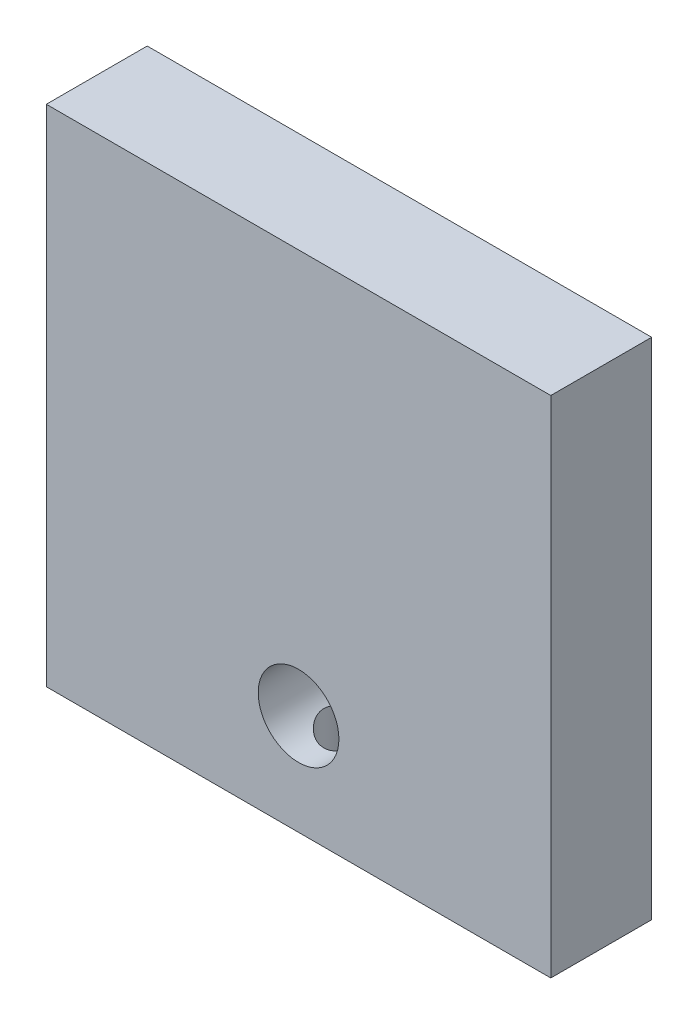
SolidWorks part; units mm, degrees
material "СТЕКЛОПЛАСТИК"
ref_plane "Спереди" through (0, 0, 0) normal (0, 0, 1) x (1, 0, 0)
ref_plane "Сверху" through (0, 0, 0) normal (0, 1, 0) x (1, 0, 0)
ref_plane "Справа" through (0, 0, 0) normal (1, 0, 0) x (0, 0, -1)
sketch "Эскиз1" plane through (0, 0, 0) normal (0, 0, 1) x (1, 0, 0)
  line L1 (0, 0) -> (50, 0)
  line L2 (0, 0) -> (0, 50)
  line L3 (0, 50) -> (50, 50)
  line L4 (50, 0) -> (50, 50)
  dimension "D1" = 50
  dimension "D2" = 50
extrude "Бобышка-Вытянуть1" add sketch "Эскиз1" along normal blind 10
sketch "Эскиз2" plane through (0, 0, 10) normal (0, 0, 1) x (1, 0, 0)
  line L0 (0, 0) -> (50, 0) construction
  line L1 (0, 50) -> (0, 0) construction
  circle A0 centre (25, 10) radius 4
  point P2 (0, 0)
  point P5 (0, 0)
  point P6 (0, 0)
  point P8 (17.9834, 9.0252)
  point P10 (0, 0)
  point P11 (0, 0)
  dimension "D1" = 8
  dimension "D2" = 10
  dimension "D3" = 25
extrude "Вырез-Вытянуть1" cut sketch "Эскиз2" against normal blind 10
sketch "Эскиз3" plane through (0, 0, 0) normal (0, -1, 0) x (1, 0, 0)
  line L0 (0, 10) -> (0, 0) construction
  line L1 (0, 0) -> (50, 0) construction
  circle A0 centre (25, 5) radius 2.5
  dimension "D1" = 5
  dimension "D2" = 25
  dimension "D3" = 5
extrude "Вырез-Вытянуть2" cut sketch "Эскиз3" against normal blind 10
